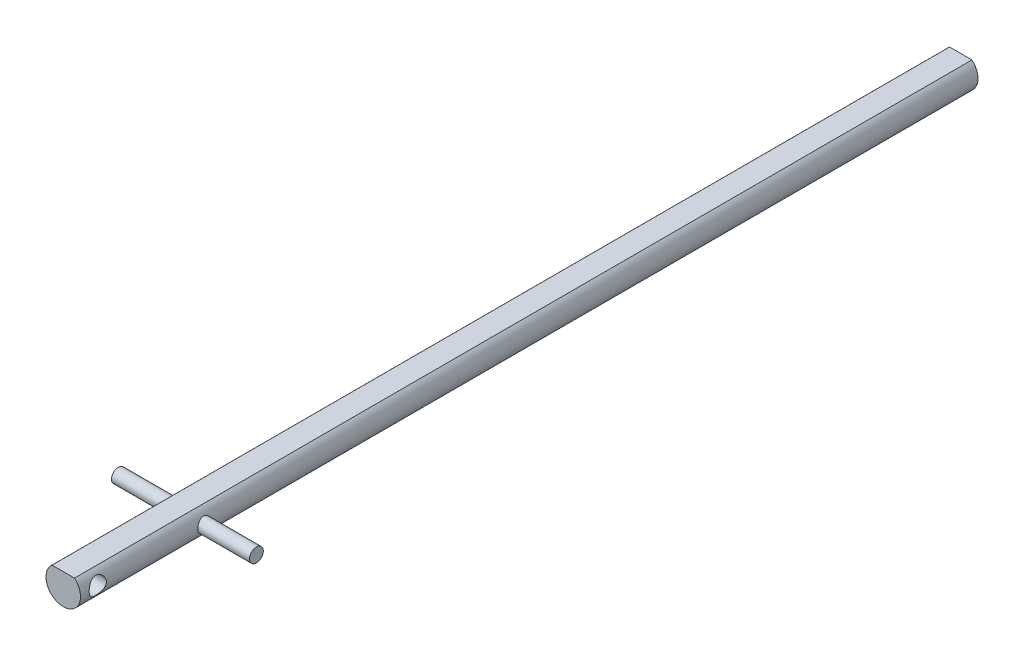
SolidWorks part; units mm, degrees
ref_plane "Plan de face" through (0, 0, 0) normal (0, 0, 1) x (1, 0, 0)
ref_plane "Plan de dessus" through (0, 0, 0) normal (0, 1, 0) x (1, 0, 0)
ref_plane "Plan de droite" through (0, 0, 0) normal (1, 0, 0) x (0, 0, -1)
sketch "Esquisse1" plane through (0, 0, 0) normal (0, 0, 1) x (1, 0, 0)
  line L0 (-3.2496, 3.8) -> (3.2496, 3.8)
  arc A0 (-3.2496, 3.8) -> (3.2496, 3.8) centre (0, 0) ccw
  dimension "D1" = 10
  dimension "D2" = 3.8
extrude "Boss.-Extru.1" add sketch "Esquisse1" along normal blind 260
sketch "Esquisse2" plane through (0, 0, 0) normal (1, 0, 0) x (0, 0, -1)
  line L0 (-260, 3.8) -> (-260, -5) construction
  circle A0 centre (-255, 0) radius 2.5
  dimension "D1" = 5
  dimension "D2" = 5
extrude "Enlèv. mat.-Extru.1" cut sketch "Esquisse2" against normal through all and the other way through all
sketch "Esquisse3" plane through (0, 0, 0) normal (1, 0, 0) x (0, 0, -1)
  line L0 (-232.6116, 124.448) -> (-225.9949, 46.6196) construction
  circle A0 centre (-224.0387, 0) radius 2
  dimension "D1" = 4
extrude "Boss.-Extru.2" add sketch "Esquisse3" along normal mid plane 40
